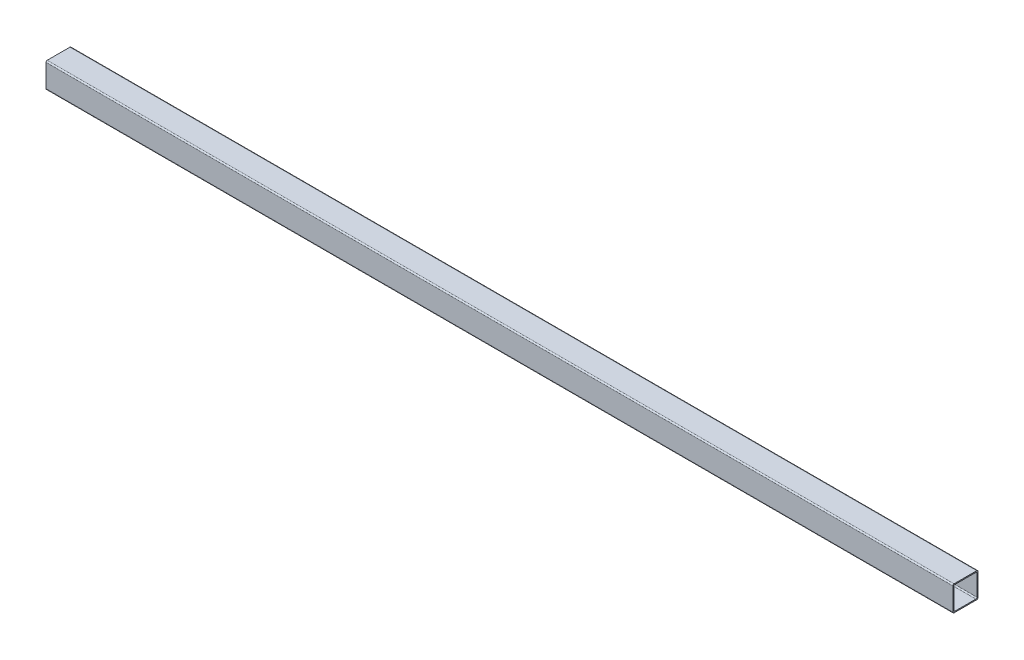
SolidWorks part; units mm, degrees
ref_plane "Front" through (0, 0, 0) normal (0, 0, 1) x (1, 0, 0)
ref_plane "Top" through (0, 0, 0) normal (0, 1, 0) x (1, 0, 0)
ref_plane "Right" through (0, 0, 0) normal (1, 0, 0) x (0, 0, -1)
sketch "Sketch1" plane through (0, 0, 0) normal (1, 0, 0) x (0, 0, -1)
  line L0 (-23.2918, 0) -> (-25.4, 0) construction
  line L1 (22.86, -25.4) -> (-22.86, -25.4) construction
  line L2 (25.4, -22.86) -> (25.4, 22.86) construction
  line L3 (22.86, 25.4) -> (-22.86, 25.4) construction
  line L4 (-25.4, -22.86) -> (-25.4, 22.86) construction
  line L5 (25.4, -25.4) -> (-25.4, 25.4) construction
  line L6 (25.4, 25.4) -> (-25.4, -25.4) construction
  line L7 (20.9626, 23.2918) -> (-20.9626, 23.2918) construction
  line L8 (23.2918, 20.9626) -> (23.2918, -20.9626) construction
  line L9 (20.9626, -23.2918) -> (-20.9626, -23.2918) construction
  line L10 (-23.2918, 20.9626) -> (-23.2918, -20.9626) construction
  line L11 (23.2918, 23.2918) -> (-23.2918, -23.2918) construction
  line L12 (23.2918, -23.2918) -> (-23.2918, 23.2918) construction
  line L13 (0, -23.2918) -> (0, -25.4) construction
  line L14 (23.2918, -20.9626) -> (23.2918, -25.4) construction
  line L15 (23.2918, 0) -> (25.4, 0) construction
  line L16 (23.2918, -25.4) -> (25.4, -25.4) construction
  arc A0 (-20.9626, -23.2918) -> (-23.2918, -20.9626) centre (-20.9626, -20.9626) cw construction
  arc A1 (23.2918, -20.9626) -> (20.9626, -23.2918) centre (20.9626, -20.9626) cw construction
  arc A2 (20.9626, 23.2918) -> (23.2918, 20.9626) centre (20.9626, 20.9626) cw construction
  arc A3 (-20.9626, 23.2918) -> (-23.2918, 20.9626) centre (-20.9626, 20.9626) ccw construction
  arc A4 (22.86, -25.4) -> (25.4, -22.86) centre (22.86, -22.86) ccw construction
  arc A5 (25.4, 22.86) -> (22.86, 25.4) centre (22.86, 22.86) ccw construction
  arc A6 (-22.86, 25.4) -> (-25.4, 22.86) centre (-22.86, 22.86) ccw construction
  arc A7 (-22.86, -25.4) -> (-25.4, -22.86) centre (-22.86, -22.86) cw construction
  point P0 (0, 0)
  point P6 (0, 0)
  dimension "D2" = 2.3292
  dimension "D3" = 2.54
  dimension "Outside Width" = 50.8
  dimension "Ouside Height" = 50.8
  dimension "Inside Height" = 46.5836
  dimension "Wall Thickness" = 2.1082
sketch "Sketch2" plane through (0, 0, 0) normal (0, 0, 1) x (1, 0, 0)
  line L0 (-914.4, 0) -> (914.4, 0) construction
  point P3 (-865.7082, 0)
  point P4 (865.7082, 0)
  dimension "Length" = 1828.8
  dimension "D1" = 48.6918
  dimension "D2" = 48.6918
sketch "Sketch4" plane through (0, 0, 0) normal (1, 0, 0) x (0, 0, -1)
  line L8 (25.4, -22.86) -> (25.4, 22.86)
  line L9 (22.86, 25.4) -> (-22.86, 25.4)
  line L10 (-25.4, -22.86) -> (-25.4, 22.86)
  line L11 (22.86, -25.4) -> (-22.86, -25.4)
  line L12 (23.2918, 20.9626) -> (23.2918, -20.9626)
  line L13 (20.9626, -23.2918) -> (-20.9626, -23.2918)
  line L14 (-23.2918, 20.9626) -> (-23.2918, -20.9626)
  line L15 (20.9626, 23.2918) -> (-20.9626, 23.2918)
  arc A8 (25.4, 22.86) -> (22.86, 25.4) centre (22.86, 22.86) ccw
  arc A9 (-22.86, 25.4) -> (-25.4, 22.86) centre (-22.86, 22.86) ccw
  arc A10 (-25.4, -22.86) -> (-22.86, -25.4) centre (-22.86, -22.86) ccw
  arc A11 (22.86, -25.4) -> (25.4, -22.86) centre (22.86, -22.86) ccw
  arc A12 (20.9626, -23.2918) -> (23.2918, -20.9626) centre (20.9626, -20.9626) ccw
  arc A13 (-23.2918, -20.9626) -> (-20.9626, -23.2918) centre (-20.9626, -20.9626) ccw
  arc A14 (-20.9626, 23.2918) -> (-23.2918, 20.9626) centre (-20.9626, 20.9626) ccw
  arc A15 (23.2918, 20.9626) -> (20.9626, 23.2918) centre (20.9626, 20.9626) ccw
extrude "Boss-Extrude1" add sketch "Sketch4" along normal up to vertex (914.4 mm away) and the other way up to vertex (914.4 mm away)
equation "\"D3@Sketch1\"=\"Outside Width@Sketch1\"*.05"
equation "\"D2@Sketch1\" = \"Inside Height@Sketch1\" * .05"
equation "\"D1@Sketch2\"=\"Outside Width@Sketch1\"-\"Wall Thickness@Sketch1\""
equation "\"D2@Sketch2\"=\"D1@Sketch2\""
